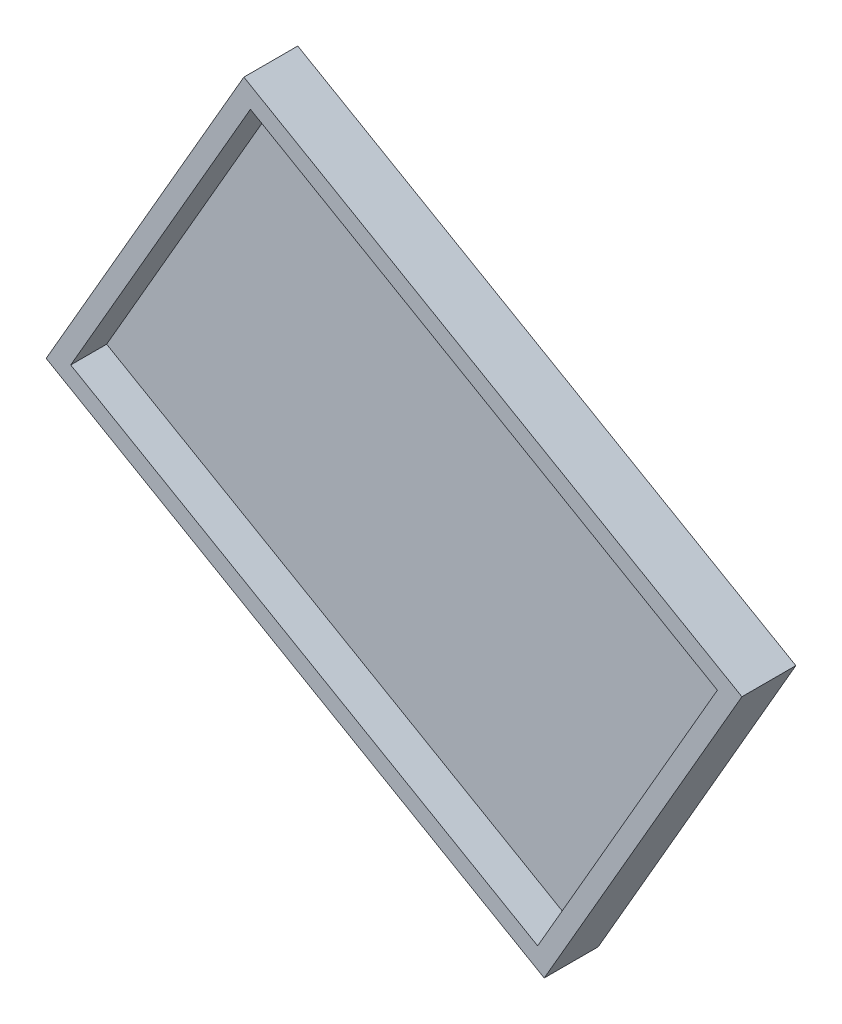
SolidWorks part; units mm, degrees
ref_plane "Front Plane" through (0, 0, 0) normal (0, 0, 1) x (1, 0, 0)
ref_plane "Top Plane" through (0, 0, 0) normal (0, 1, 0) x (1, 0, 0)
ref_plane "Right Plane" through (0, 0, 0) normal (1, 0, 0) x (0, 0, -1)
sketch "Sketch1" plane through (0, 0, 0) normal (0, 0, 1) x (1, 0, 0)
  line L18 (75.1314, 20.1314) -> (20.1314, -75.1314)
  line L19 (213.6955, -59.8686) -> (75.1314, 20.1314)
  line L20 (158.6955, -155.1314) -> (213.6955, -59.8686)
  line L21 (20.1314, -75.1314) -> (158.6955, -155.1314)
extrude "Boss-Extrude1" add sketch "Sketch1" along normal blind 5
sketch "Sketch2" plane through (0, 0, 5) normal (0, 0, 1) x (1, 0, 0)
  line L8 (26.9615, -73.3013) -> (156.8653, -148.3013)
  line L9 (156.8653, -148.3013) -> (206.8653, -61.6987)
  line L10 (206.8653, -61.6987) -> (76.9615, 13.3013)
  line L11 (76.9615, 13.3013) -> (26.9615, -73.3013)
  line L12 (26.9615, -73.3013) -> (156.8653, -148.3013)
  line L13 (156.8653, -148.3013) -> (206.8653, -61.6987)
  line L14 (206.8653, -61.6987) -> (76.9615, 13.3013)
  line L15 (76.9615, 13.3013) -> (26.9615, -73.3013)
  line L26 (158.6955, -155.1314) -> (213.6955, -59.8686)
  line L27 (20.1314, -75.1314) -> (158.6955, -155.1314)
  line L28 (75.1314, 20.1314) -> (20.1314, -75.1314)
  line L29 (213.6955, -59.8686) -> (75.1314, 20.1314)
  line L30 (158.6955, -155.1314) -> (213.6955, -59.8686)
  line L31 (20.1314, -75.1314) -> (158.6955, -155.1314)
  line L32 (75.1314, 20.1314) -> (20.1314, -75.1314)
  line L33 (213.6955, -59.8686) -> (75.1314, 20.1314)
  dimension "D1" = 5
  dimension "D2" = 0
extrude "Boss-Extrude2" add sketch "Sketch2" along normal blind 10
